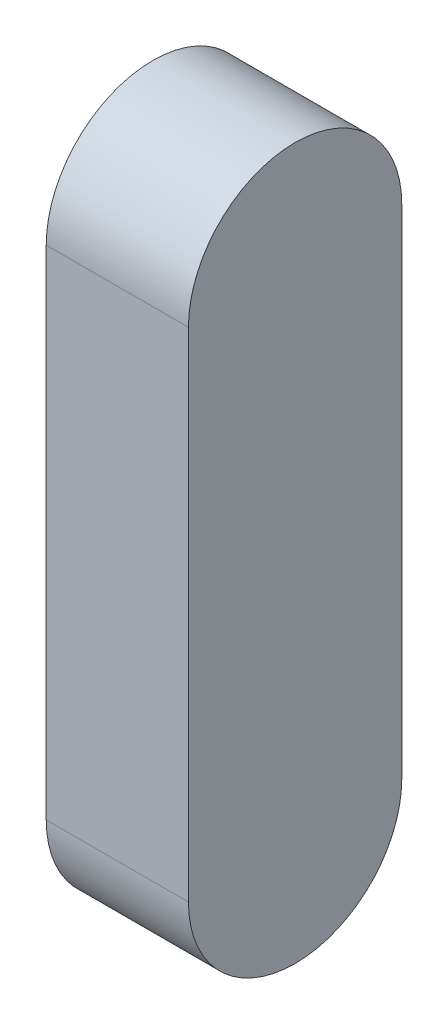
SolidWorks part; units mm, degrees
ref_plane "前视基准面" through (0, 0, 0) normal (0, 0, 1) x (1, 0, 0)
ref_plane "上视基准面" through (0, 0, 0) normal (0, 1, 0) x (1, 0, 0)
ref_plane "右视基准面" through (0, 0, 0) normal (1, 0, 0) x (0, 0, -1)
other "Configuration Table"
sketch "草图1" plane through (0, 0, 0) normal (1, 0, 0) x (0, 0, -1)
  line L0 (0, 0) -> (0, -70) construction
  line L1 (15, 0) -> (15, -70)
  line L2 (-15, 0) -> (-15, -70)
  arc A0 (15, 0) -> (-15, 0) centre (0, 0) ccw
  arc A1 (-15, -70) -> (15, -70) centre (0, -70) ccw
  point P3 (0, -35)
  dimension "D2" = 15
  dimension "D1" = 70
extrude "凸台-拉伸1" add sketch "草图1" along normal blind 20
